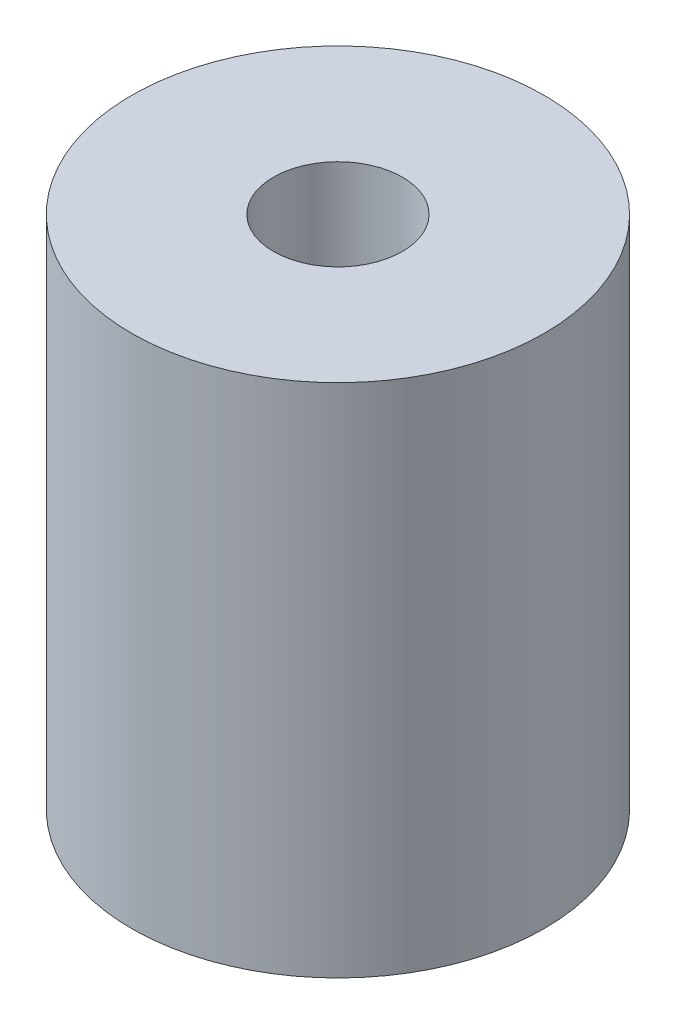
SolidWorks part; units mm, degrees
ref_plane "前基準面" through (0, 0, 0) normal (0, 0, 1) x (1, 0, 0)
ref_plane "上基準面" through (0, 0, 0) normal (0, 1, 0) x (1, 0, 0)
ref_plane "右基準面" through (0, 0, 0) normal (1, 0, 0) x (0, 0, -1)
sketch "草圖1" plane through (0, 0, 0) normal (0, 1, 0) x (1, 0, 0)
  circle A0 centre (0, 0) radius 6
  dimension "D1" = 12
extrude "填料-伸長1" add sketch "草圖1" along normal blind 40
sketch "草圖2" plane through (0, 40, 0) normal (0, 1, 0) x (1, 0, 0)
  circle A0 centre (0, 0) radius 5
  dimension "D1" = 10
extrude "除料-伸長2" cut sketch "草圖2" against normal blind 30
sketch "草圖3" plane through (0, 0, 0) normal (0, -1, 0) x (1, 0, 0)
  circle A0 centre (0, 0) radius 2.5
  dimension "D1" = 5
extrude "除料-伸長4" cut sketch "草圖3" against normal blind 10
sketch "草圖5" plane through (0, 0, 0) normal (0, 1, 0) x (1, 0, 0)
  circle A0 centre (0, 0) radius 6
extrude "伸長-薄件1" add sketch "草圖5" along normal blind 40 thin
